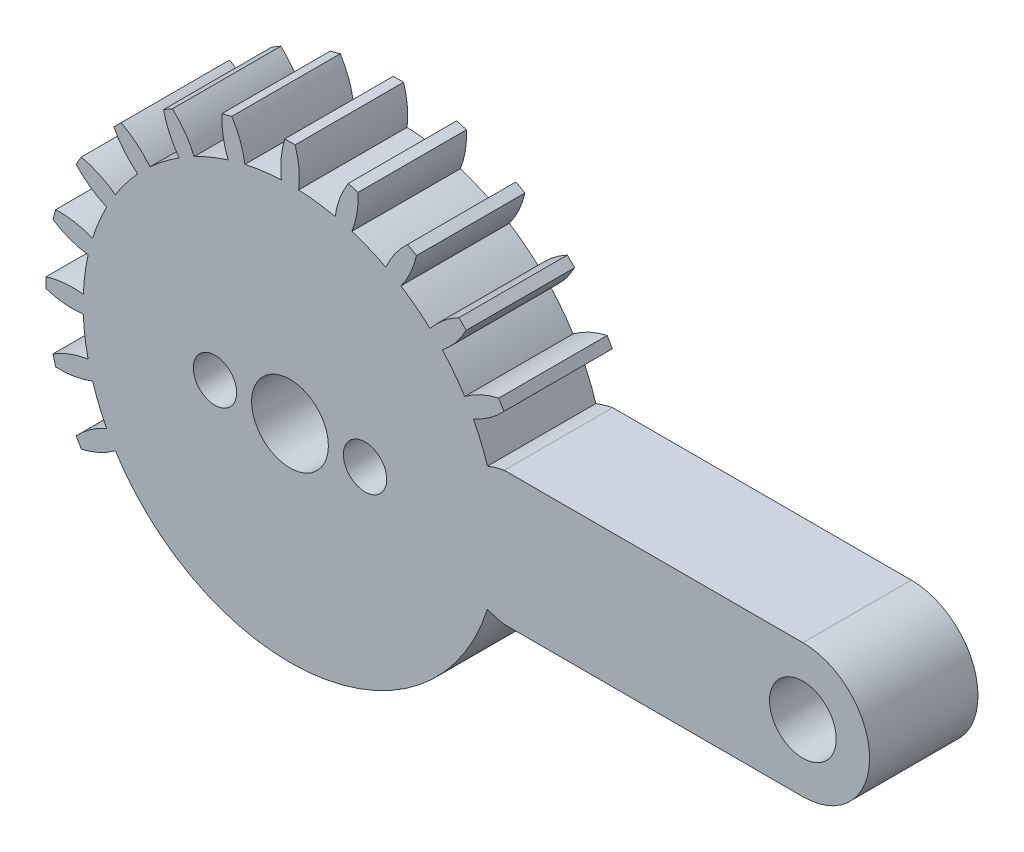
SolidWorks part; units mm, degrees
ref_plane "Front Plane" through (0, 0, 0) normal (0, 0, 1) x (1, 0, 0)
ref_plane "Top Plane" through (0, 0, 0) normal (0, 1, 0) x (1, 0, 0)
ref_plane "Right Plane" through (0, 0, 0) normal (1, 0, 0) x (0, 0, -1)
sketch "Sketch1" plane through (0, 0, 0) normal (0, 0, 1) x (1, 0, 0)
  line L0 (0, -14.63) -> (0, 14.63) construction
  line L1 (-0.31, 14.63) -> (0.31, 14.63)
  line L2 (3.4871, 14.2117) -> (4.086, 14.0513)
  line L3 (7.0465, 12.825) -> (7.5835, 12.515)
  line L4 (10.1258, 10.5642) -> (10.5642, 10.1258)
  line L5 (12.515, 7.5835) -> (12.825, 7.0465)
  line L6 (14.0513, 4.086) -> (14.2117, 3.4871)
  line L7 (14.63, 0.31) -> (14.63, -0.31)
  line L8 (14.2117, -3.4871) -> (14.0513, -4.086)
  line L9 (12.825, -7.0465) -> (12.515, -7.5835)
  line L10 (10.5642, -10.1258) -> (10.1258, -10.5642)
  line L11 (7.5835, -12.515) -> (7.0465, -12.825)
  line L12 (4.086, -14.0513) -> (3.4871, -14.2117)
  line L13 (0.31, -14.63) -> (-0.31, -14.63)
  line L14 (-3.4871, -14.2117) -> (-4.086, -14.0513)
  line L15 (-7.0465, -12.825) -> (-7.5835, -12.515)
  line L16 (-10.1258, -10.5642) -> (-10.5642, -10.1258)
  line L17 (-12.515, -7.5835) -> (-12.825, -7.0465)
  line L18 (-14.0513, -4.086) -> (-14.2117, -3.4871)
  line L19 (-14.63, -0.31) -> (-14.63, 0.31)
  line L20 (-14.2117, 3.4871) -> (-14.0513, 4.086)
  line L21 (-12.825, 7.0465) -> (-12.515, 7.5835)
  line L22 (-10.5642, 10.1258) -> (-10.1258, 10.5642)
  line L23 (-7.5835, 12.515) -> (-7.0465, 12.825)
  line L24 (-4.086, 14.0513) -> (-3.4871, 14.2117)
  line L25 (30.75, -4) -> (30.75, 4) construction
  line L26 (30.75, 4) -> (11.7424, 4)
  line L27 (30.75, 0) -> (0, 0) construction
  line L28 (30.75, -4) -> (11.7424, -4)
  circle A0 centre (0, 0) radius 12.405
  circle A1 centre (0, 0) radius 1.75
  circle A2 centre (30.75, 0) radius 2
  arc A3 (-0.52, 12.3941) -> (-0.31, 14.63) centre (4.8438, 13.0181) cw
  arc A4 (-0.52, 16.8659) -> (-0.31, 14.63) centre (4.8438, 16.2419) ccw
  arc A5 (0.52, 12.3941) -> (0.31, 14.63) centre (-4.8438, 13.0181) ccw
  arc A6 (2.7055, 12.1064) -> (3.4871, 14.2117) centre (8.0481, 11.3209) cw
  arc A7 (3.7101, 11.8372) -> (4.086, 14.0513) centre (-1.3094, 13.8282) ccw
  arc A8 (5.7467, 10.9936) -> (7.0465, 12.825) centre (10.7039, 8.8521) cw
  arc A9 (6.6474, 10.4736) -> (7.5835, 12.515) centre (2.3142, 13.6959) ccw
  arc A10 (8.3963, 9.1316) -> (10.1258, 10.5642) centre (12.6303, 5.7801) cw
  arc A11 (9.1316, 8.3963) -> (10.5642, 10.1258) centre (5.7801, 12.6303) ccw
  arc A12 (10.4736, 6.6474) -> (12.515, 7.5835) centre (13.6959, 2.3142) cw
  arc A13 (10.9936, 5.7467) -> (12.825, 7.0465) centre (8.8521, 10.7039) ccw
  arc A14 (11.8372, 3.7101) -> (14.0513, 4.086) centre (13.8282, -1.3094) cw
  arc A15 (12.1064, 2.7055) -> (14.2117, 3.4871) centre (11.3209, 8.0481) ccw
  arc A16 (12.3941, 0.52) -> (14.63, 0.31) centre (13.0181, -4.8438) cw
  arc A17 (12.3941, -0.52) -> (14.63, -0.31) centre (13.0181, 4.8438) ccw
  arc A18 (12.1064, -2.7055) -> (14.2117, -3.4871) centre (11.3209, -8.0481) cw
  arc A19 (11.8372, -3.7101) -> (14.0513, -4.086) centre (13.8282, 1.3094) ccw
  arc A20 (10.9936, -5.7467) -> (12.825, -7.0465) centre (8.8521, -10.7039) cw
  arc A21 (10.4736, -6.6474) -> (12.515, -7.5835) centre (13.6959, -2.3142) ccw
  arc A22 (9.1316, -8.3963) -> (10.5642, -10.1258) centre (5.7801, -12.6303) cw
  arc A23 (8.3963, -9.1316) -> (10.1258, -10.5642) centre (12.6303, -5.7801) ccw
  arc A24 (6.6474, -10.4736) -> (7.5835, -12.515) centre (2.3142, -13.6959) cw
  arc A25 (5.7467, -10.9936) -> (7.0465, -12.825) centre (10.7039, -8.8521) ccw
  arc A26 (3.7101, -11.8372) -> (4.086, -14.0513) centre (-1.3094, -13.8282) cw
  arc A27 (2.7055, -12.1064) -> (3.4871, -14.2117) centre (8.0481, -11.3209) ccw
  arc A28 (0.52, -12.3941) -> (0.31, -14.63) centre (-4.8438, -13.0181) cw
  arc A29 (-0.52, -12.3941) -> (-0.31, -14.63) centre (4.8438, -13.0181) ccw
  arc A30 (-2.7055, -12.1064) -> (-3.4871, -14.2117) centre (-8.0481, -11.3209) cw
  arc A31 (-3.7101, -11.8372) -> (-4.086, -14.0513) centre (1.3094, -13.8282) ccw
  arc A32 (-5.7467, -10.9936) -> (-7.0465, -12.825) centre (-10.7039, -8.8521) cw
  arc A33 (-6.6474, -10.4736) -> (-7.5835, -12.515) centre (-2.3142, -13.6959) ccw
  arc A34 (-8.3963, -9.1316) -> (-10.1258, -10.5642) centre (-12.6303, -5.7801) cw
  arc A35 (-9.1316, -8.3963) -> (-10.5642, -10.1258) centre (-5.7801, -12.6303) ccw
  arc A36 (-10.4736, -6.6474) -> (-12.515, -7.5835) centre (-13.6959, -2.3142) cw
  arc A37 (-10.9936, -5.7467) -> (-12.825, -7.0465) centre (-8.8521, -10.7039) ccw
  arc A38 (-11.8372, -3.7101) -> (-14.0513, -4.086) centre (-13.8282, 1.3094) cw
  arc A39 (-12.1064, -2.7055) -> (-14.2117, -3.4871) centre (-11.3209, -8.0481) ccw
  arc A40 (-12.3941, -0.52) -> (-14.63, -0.31) centre (-13.0181, 4.8438) cw
  arc A41 (-12.3941, 0.52) -> (-14.63, 0.31) centre (-13.0181, -4.8438) ccw
  arc A42 (-12.1064, 2.7055) -> (-14.2117, 3.4871) centre (-11.3209, 8.0481) cw
  arc A43 (-11.8372, 3.7101) -> (-14.0513, 4.086) centre (-13.8282, -1.3094) ccw
  arc A44 (-10.9936, 5.7467) -> (-12.825, 7.0465) centre (-8.8521, 10.7039) cw
  arc A45 (-10.4736, 6.6474) -> (-12.515, 7.5835) centre (-13.6959, 2.3142) ccw
  arc A46 (-9.1316, 8.3963) -> (-10.5642, 10.1258) centre (-5.7801, 12.6303) cw
  arc A47 (-8.3963, 9.1316) -> (-10.1258, 10.5642) centre (-12.6303, 5.7801) ccw
  arc A48 (-6.6474, 10.4736) -> (-7.5835, 12.515) centre (-2.3142, 13.6959) cw
  arc A49 (-5.7467, 10.9936) -> (-7.0465, 12.825) centre (-10.7039, 8.8521) ccw
  arc A50 (-3.7101, 11.8372) -> (-4.086, 14.0513) centre (1.3094, 13.8282) cw
  arc A51 (-2.7055, 12.1064) -> (-3.4871, 14.2117) centre (-8.0481, 11.3209) ccw
  arc A52 (30.75, -4) -> (30.75, 4) centre (30.75, 0) ccw
  point P12 (0, 0)
  point P158 (0, 0)
  point P160 (30.75, 0)
  dimension "D1" = 24.81
  dimension "D2" = 3.5
  dimension "D3" = 4
  dimension "D6" = 5.4
  dimension "D10" = 8
  dimension "D4" = 30.75
  dimension "D5" = 29.26
  dimension "D7" = 0.31
  dimension "D8" = 1.04
  dimension "D9" = 24
extrude "Boss-Extrude1" add sketch "Sketch1" along normal blind 6.5 contours L28 A52 L26 L6 A15 A0 A16 L7 A17 A18 L8 A2 | A0 | A0 A13 L5 A12 | A0 A11 L4 A10 | A0 A9 L3 A8 | A0 A7 L2 A6 | A0 A5 L1 A3 | A0 A51 L24 A50 | A0 A49 L23 A48 | A0 A47 L22 A46 | A0 A45 L21 A44 | A0 A43 L20 A42 | A0 A41 L19 A40 | A0 A39 L18 A38 | A0 A15 L6 L26 A14 | A0 A17 L7 A16 | A0 A19 L28 L8 A18 | A0 A37 L17 A36
sketch "Sketch2" plane through (0, 0, 6.5) normal (0, 0, 1) x (1, 0, 0)
  line L0 (-4.5, 0) -> (4.5, 0) construction
  circle A0 centre (0, 0) radius 2.3
  circle A1 centre (4.5, 0) radius 1.3
  circle A2 centre (-4.5, 0) radius 1.3
  point P5 (0, 0)
  dimension "D2" = 2.6
  dimension "D3" = 2.6
  dimension "D4" = 4.6
  dimension "D1" = 9
extrude "Cut-Extrude1" cut sketch "Sketch2" against normal through all
